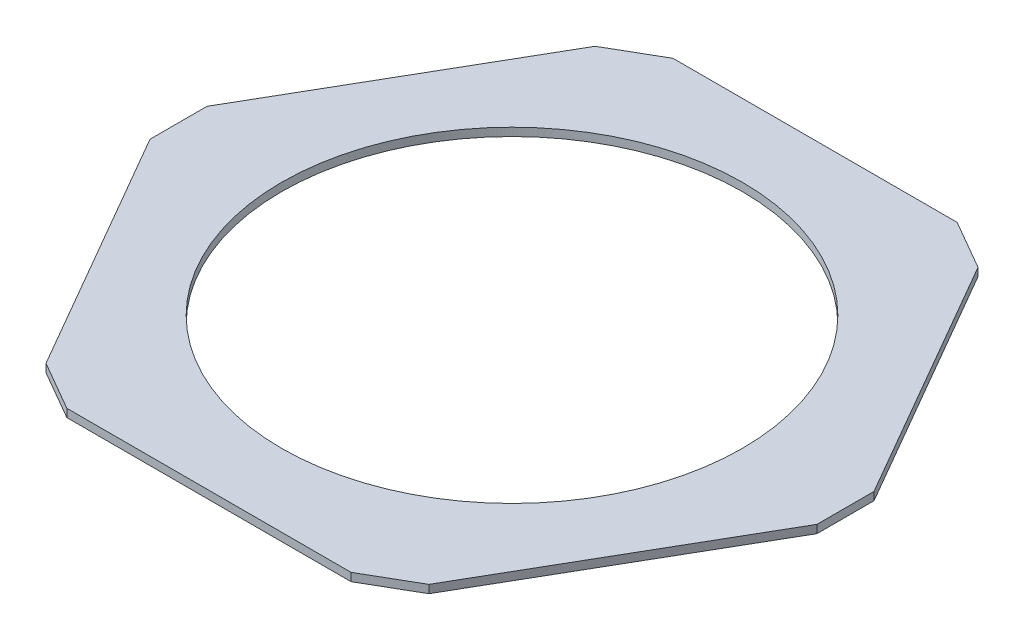
SolidWorks part; units mm, degrees
material "Ti-6Al-4VSolution treated and aged (SS)"
ref_plane "Front Plane" through (0, 0, 0) normal (0, 0, 1) x (1, 0, 0)
ref_plane "Top Plane" through (0, 0, 0) normal (0, 1, 0) x (1, 0, 0)
ref_plane "Right Plane" through (0, 0, 0) normal (1, 0, 0) x (0, 0, -1)
sketch "Sketch1" plane through (0, 0, 0) normal (0, 1, 0) x (1, 0, 0)
  line L10 (438.3179, 934.9709) -> (590.5496, 847.0799)
  line L13 (1028.8675, 87.891) -> (590.5496, 847.0799)
  line L14 (438.3179, 934.9709) -> (-438.3179, 934.9709)
  line L15 (-590.5496, 847.0799) -> (-1028.8675, 87.891)
  line L16 (-1028.8675, -87.891) -> (-590.5496, -847.0799)
  line L17 (-438.3179, -934.9709) -> (438.3179, -934.9709)
  line L18 (590.5496, -847.0799) -> (1028.8675, -87.891)
  line L19 (1028.8675, 87.891) -> (1028.8675, -87.891)
  line L20 (590.5496, -847.0799) -> (438.3179, -934.9709)
  line L21 (-438.3179, -934.9709) -> (-590.5496, -847.0799)
  line L22 (-1028.8675, -87.891) -> (-1028.8675, 87.891)
  line L23 (-590.5496, 847.0799) -> (-438.3179, 934.9709)
  point P21 (0, 0)
  dimension "D4" = 876.6359
  dimension "D1" = 30
  dimension "D2" = 6
  dimension "D3" = 2057.735
  dimension "D5" = 0
extrude "Boss-Extrude1" add sketch "Sketch1" along normal blind 25
sketch "Sketch2" plane through (0, 0, 0) normal (0, 1, 0) x (1, 0, 0)
  circle A0 centre (0, 0) radius 710.8713
  dimension "D1" = 1421.7426
extrude "Cut-Extrude4" cut sketch "Sketch2" along normal up to next
